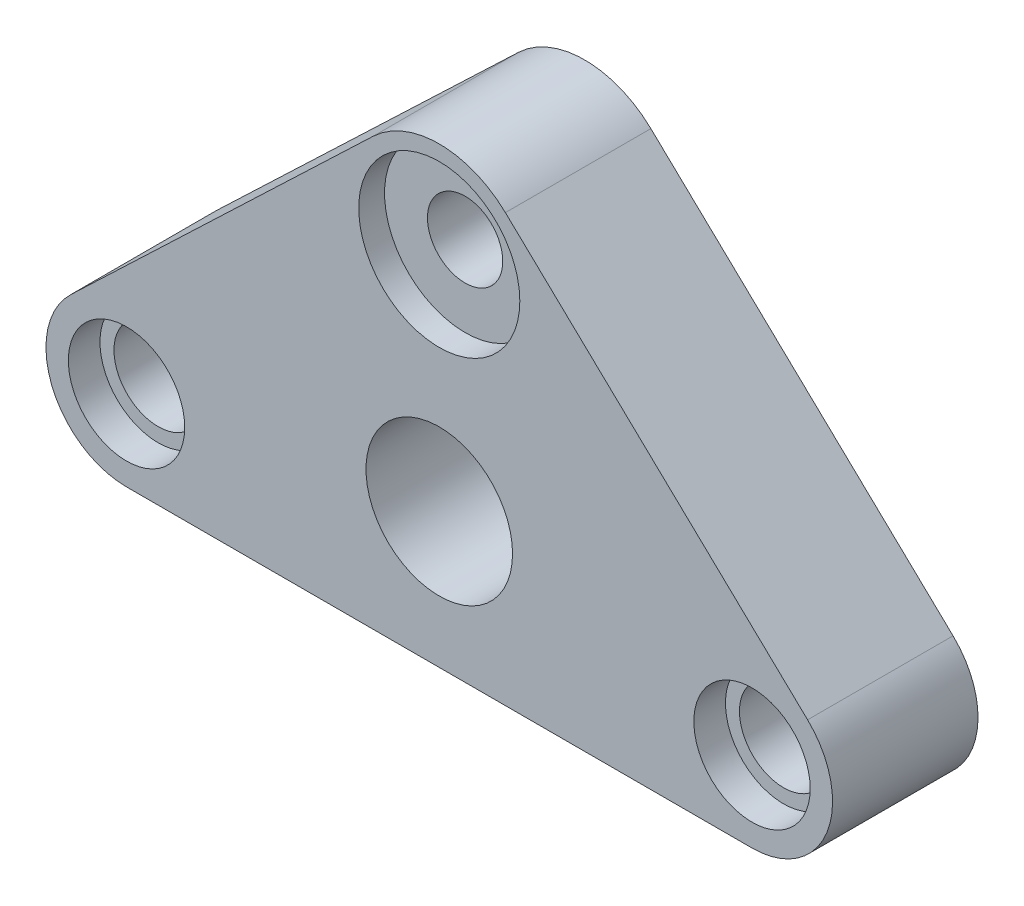
SolidWorks part; units mm, degrees
ref_plane "Ön Düzlem" through (0, 0, 0) normal (0, 0, 1) x (1, 0, 0)
ref_plane "Üst Düzlem" through (0, 0, 0) normal (0, 1, 0) x (1, 0, 0)
ref_plane "Sağ Düzlem" through (0, 0, 0) normal (1, 0, 0) x (0, 0, -1)
sketch "Sketch1" plane through (0, 0, 0) normal (0, 0, 1) x (1, 0, 0)
  line L0 (9.0918, 9.5352) -> (50.6426, -30.0832)
  line L1 (-9.0918, 9.5352) -> (-50.6426, -30.0832)
  line L2 (-43, -49.1736) -> (43, -49.1736)
  circle A0 centre (0, 0) radius 5.175
  circle A1 centre (43, -38.0986) radius 6.075
  circle A2 centre (-43, -38.0986) radius 6.075
  arc A3 (9.0918, 9.5352) -> (-9.0918, 9.5352) centre (0, 0) ccw
  arc A4 (43, -49.1736) -> (50.6426, -30.0832) centre (43, -38.0986) ccw
  arc A5 (-50.6426, -30.0832) -> (-43, -49.1736) centre (-43, -38.0986) ccw
  circle A6 centre (-43, -38.0986) radius 11.075 construction
  circle A7 centre (0, 0) radius 13.175 construction
  circle A8 centre (43, -38.0986) radius 11.075 construction
  dimension "D1" = 10.35
  dimension "D4" = 12.15
  dimension "D2" = 57.45
  dimension "D3" = 57.45
  dimension "D5" = 86
  dimension "D6" = 8
  dimension "D7" = 5
  dimension "D8" = 5
extrude "Boss-Extrude1" add sketch "Sketch1" along normal blind 20
sketch "Sketch2" plane through (0, 0, 20) normal (0, 0, 1) x (1, 0, 0)
  circle A0 centre (0, 0) radius 11.075
  dimension "D1" = 22.15
extrude "Cut-Extrude1" cut sketch "Sketch2" against normal blind 3.55
sketch "Sketch3" plane through (0, 0, 0) normal (0, 0, -1) x (-1, 0, 0)
  circle A0 centre (43, -38.0986) radius 8
  circle A1 centre (-43, -38.0986) radius 8
  dimension "D1" = 16
  dimension "D2" = 16
extrude "Cut-Extrude2" cut sketch "Sketch3" against normal blind 4.35
sketch "Sketch4" plane through (0, 0, 20) normal (0, 0, 1) x (1, 0, 0)
  circle A0 centre (-43, -38.0986) radius 8
  circle A1 centre (43, -38.0986) radius 8
  dimension "D1" = 16
  dimension "D2" = 16
extrude "Cut-Extrude3" cut sketch "Sketch4" against normal blind 4.35
sketch "Sketch5" plane through (0, 0, 20) normal (0, 0, 1) x (1, 0, 0)
  line L0 (27.9195, -30.5936) -> (-25.5998, -30.5936) construction
  line L1 (-43, -49.1736) -> (43, -49.1736) construction
  circle A0 centre (0, -30.5936) radius 10.075
  circle A2 centre (43, -38.0986) radius 6.075 construction
  dimension "D1" = 20.15
  dimension "D2" = 12.15
  dimension "D3" = 18.58
extrude "Cut-Extrude4" cut sketch "Sketch5" against normal blind 15
sketch "Sketch6" plane through (0, 0, 5) normal (0, 0, 1) x (1, 0, 0)
  circle A0 centre (0, -30.5936) radius 1.75
  dimension "D1" = 3.5
extrude "Cut-Extrude5" cut sketch "Sketch6" against normal up to surface (5 mm away) up to face at (35, -38.0986, 0)
